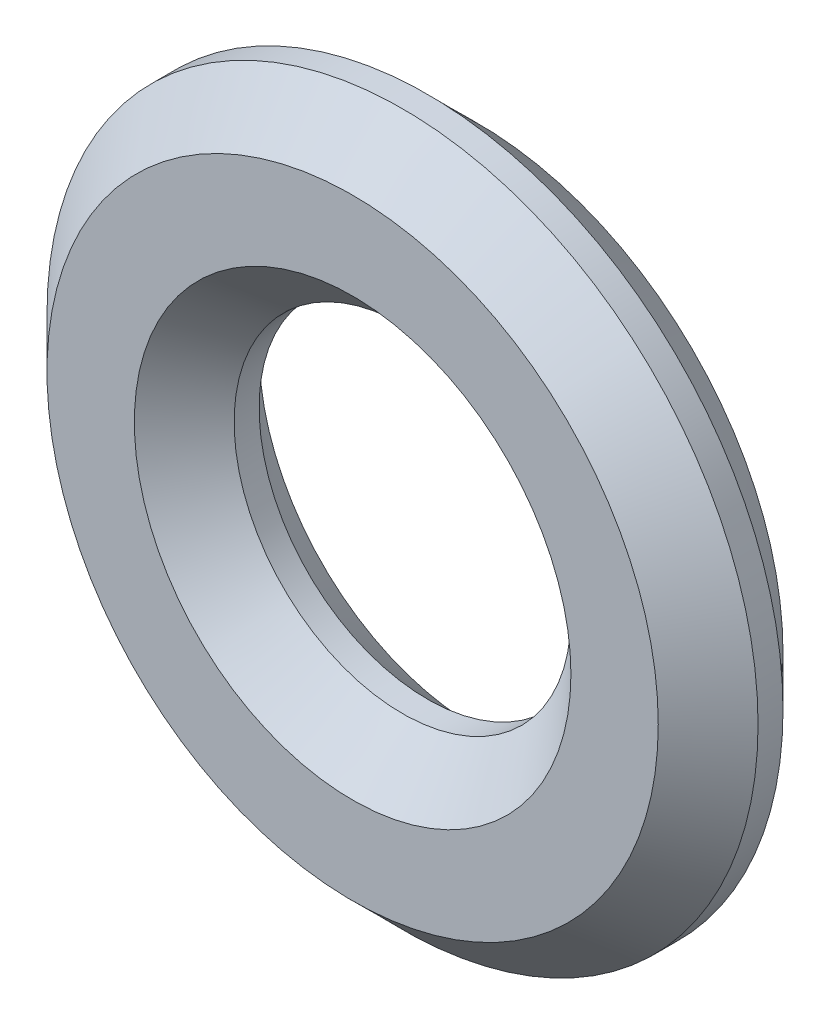
SolidWorks part; units mm, degrees
ref_plane "Plano frontal" through (0, 0, 0) normal (0, 0, 1) x (1, 0, 0)
ref_plane "Plano superior" through (0, 0, 0) normal (0, 1, 0) x (1, 0, 0)
ref_plane "Plano direito" through (0, 0, 0) normal (1, 0, 0) x (0, 0, -1)
sketch "Esboço1" plane through (0, 0, 0) normal (0, 0, 1) x (1, 0, 0)
  circle A0 centre (0, 0) radius 5.7
  circle A1 centre (0, 0) radius 2.7
  dimension "D1" = 5.4
  dimension "D2" = 3
extrude "Ressalto-extrusão1" add sketch "Esboço1" along normal blind 2
chamfer "Chanfro1" distance 0.8 angle 45 4 edges at (2.7, 0, 0) (5.7, 0, 0) (2.7, 0, 2) (5.7, 0, 2)
